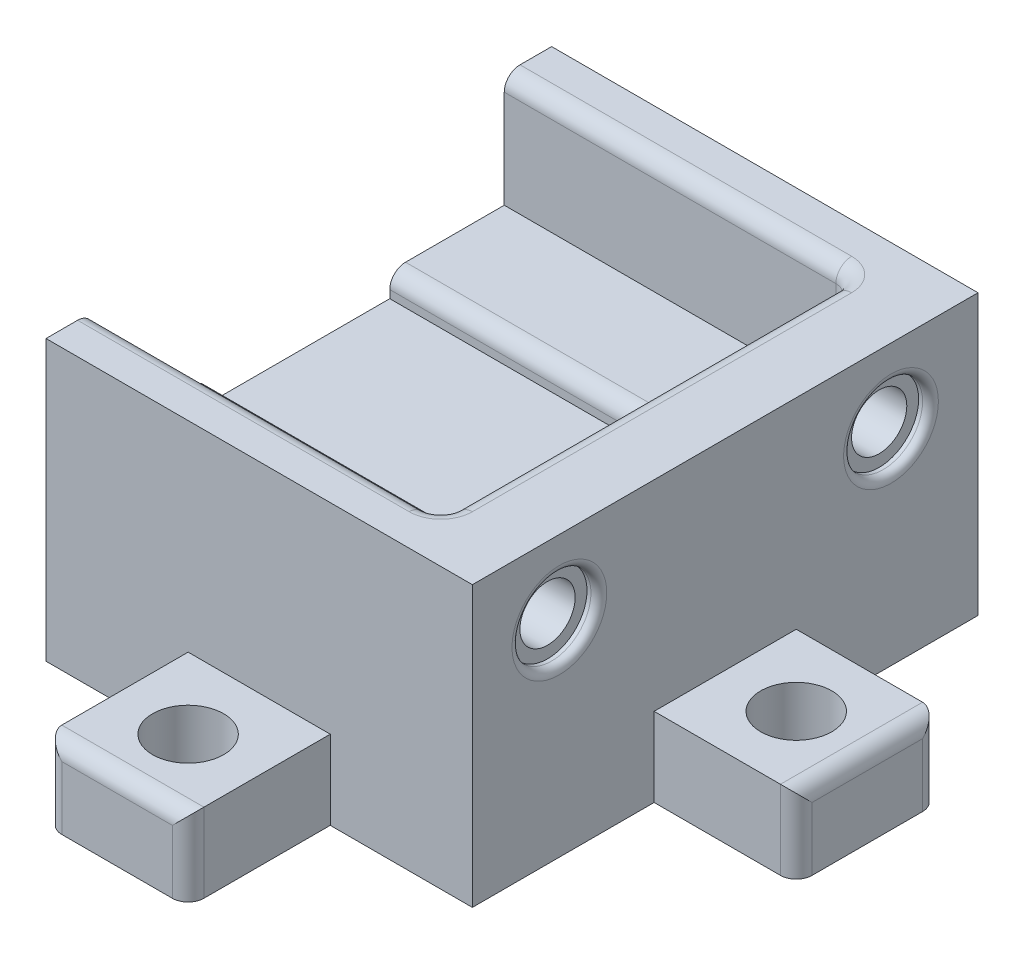
SolidWorks part; units mm, degrees
ref_plane "Front" through (0, 0, 0) normal (0, 0, 1) x (1, 0, 0)
ref_plane "Top" through (0, 0, 0) normal (0, 1, 0) x (1, 0, 0)
ref_plane "Right" through (0, 0, 0) normal (1, 0, 0) x (0, 0, -1)
sketch "Sketch1" plane through (0, 0, 0) normal (1, 0, 0) x (0, 0, -1)
  line L0 (-13.0089, 0) -> (13.0089, 0)
  line L1 (13.0089, 0) -> (13.0089, 10.5)
  line L2 (13.0089, 10.5) -> (5.7589, 10.5)
  line L3 (5.7589, 10.5) -> (5.7589, 9)
  line L4 (5.7589, 9) -> (-5.7589, 9)
  line L5 (-5.7589, 9) -> (-5.7589, 10.5)
  line L6 (-5.7589, 10.5) -> (-13.0089, 10.5)
  line L7 (-13.0089, 10.5) -> (-13.0089, 0)
  dimension "D1" = 10.5
  dimension "D2" = 7.25
  dimension "D3" = 26.0178
  dimension "D4" = 1.5
extrude "Boss-Extrude1" add sketch "Sketch1" along normal mid plane 22
sketch "Sketch3" plane through (0, 0, 0) normal (0, -1, 0) x (1, 0, 0)
  line L1 (-11, -13.0089) -> (11, -13.0089)
  line L2 (-11, -13.0089) -> (-11, -16.0089)
  line L3 (-11, -16.0089) -> (11, -16.0089)
  line L4 (11, -13.0089) -> (11, -16.0089)
  line L5 (-11, 13.0089) -> (11, 13.0089)
  line L6 (-11, 13.0089) -> (-11, 16.0089)
  line L7 (-11, 16.0089) -> (11, 16.0089)
  line L8 (11, 13.0089) -> (11, 16.0089)
  dimension "D1" = 3
  dimension "D2" = 22
  dimension "D3" = 3
  dimension "D4" = 22
extrude "Boss-Extrude2" add sketch "Sketch3" against normal blind 17.7
sketch "Sketch4" plane through (11, 0, 0) normal (1, 0, 0) x (0, 0, -1)
  line L0 (0, 0) -> (0, 17.7) construction
  line L1 (-16.0089, 0) -> (16.0089, 0) construction
  line L2 (-8.8, 17.7) -> (-16.0089, 17.7)
  line L3 (-16.0089, 17.7) -> (-16.0089, 0) construction
  line L4 (-16.0089, 17.7) -> (-16.0089, 0)
  line L5 (-16.0089, 0) -> (16.0089, 0)
  line L6 (16.0089, 0) -> (16.0089, 17.7)
  line L7 (16.0089, 17.7) -> (16.0089, 0) construction
  line L8 (16.0089, 17.7) -> (-8.8, 17.7)
extrude "Boss-Extrude3" add sketch "Sketch4" along normal blind 5
sketch "Sketch5" plane through (16, 0, 0) normal (1, 0, 0) x (0, 0, -1)
  line L0 (-16.0089, 13) -> (-10.5, 13) construction
  line L1 (-16.0089, 17.7) -> (-16.0089, 0) construction
  line L2 (-10.5, 13) -> (-10.5, 0) construction
  line L3 (-16.0089, 0) -> (16.0089, 0) construction
  line L4 (0, 0) -> (0, 17.7) construction
  line L5 (16.0089, 17.7) -> (-16.0089, 17.7) construction
  circle A0 centre (-10.5, 13) radius 1.75
  circle A1 centre (10.5, 13) radius 1.75
  dimension "D3" = 3.5
  dimension "D1" = 5.5089
  dimension "D2" = 13
extrude "Cut-Extrude1" cut sketch "Sketch5" against normal through all
sketch "Sketch6" plane through (0, 0, 0) normal (0, -1, 0) x (1, 0, 0)
  line L0 (16, 16.0089) -> (16, -16.0089) construction
  line L5 (0, 0) -> (16, 0) construction
  line L13 (16, 4.5) -> (25, 4.5)
  line L15 (7, 16.0089) -> (-2, 16.0089)
  line L20 (7, 16.0089) -> (7, 25.0089)
  line L21 (7, 25.0089) -> (-2, 25.0089)
  line L22 (-2, 16.0089) -> (-2, 25.0089)
  line L23 (16, 4.5) -> (16, -4.5)
  line L24 (16, -4.5) -> (25, -4.5)
  line L25 (25, 4.5) -> (25, -4.5)
  line L26 (16, 16.0089) -> (-11, 16.0089) construction
  point P12 (2.5, 16.0089)
  dimension "D1" = 9
  dimension "D2" = 9
  dimension "D3" = 9
  dimension "D4" = 9
extrude "Boss-Extrude4" add sketch "Sketch6" against normal blind 5
sketch "Sketch7" plane through (0, 5, 0) normal (0, 1, 0) x (1, 0, 0)
  line L0 (25, 0) -> (7, 0) construction
  line L2 (2.5, -16.0089) -> (2.5, -25.0089) construction
  line L3 (20.5, 4.5) -> (20.5, -4.5) construction
  line L4 (-2, -16.0089) -> (7, -16.0089) construction
  line L5 (7, -25.0089) -> (-2, -25.0089) construction
  line L7 (7, -4.5) -> (7, 4.5) construction
  line L8 (25, 4.5) -> (25, -4.5) construction
  line L9 (-2, -20.5089) -> (7, -20.5089) construction
  line L10 (16, 4.5) -> (25, 4.5) construction
  line L11 (25, -4.5) -> (16, -4.5) construction
  line L12 (-2, -25.0089) -> (-2, -16.0089) construction
  line L15 (7, -16.0089) -> (7, -25.0089) construction
  circle A0 centre (20.5, 0) radius 2.25
  circle A1 centre (2.5, -20.5089) radius 2.25
  point P5 (7, 0)
  point P11 (25, 0)
  point P23 (2.5, -20.5089)
  point P29 (20.5, 4.5)
  dimension "D1" = 4.5
extrude "Cut-Extrude2" cut sketch "Sketch7" against normal through all
fillet "Fillet1" radius 1 13 edges at (2.5, 5, 25.0089) (0, 10.5, 5.7589) (0, 10.5, -5.7589) (25, 5, 0) (0, 17.7, 13.0089) (11, 17.7, 0) (0, 17.7, -13.0089) (11, 14.1, 13.0089) (11, 14.1, -13.0089) (25, 2.5, 4.5) (25, 2.5, -4.5) (7, 2.5, 25.0089) (-2, 2.5, 25.0089)
sketch "Sketch8" plane through (16, 0, 0) normal (1, 0, 0) x (0, 0, -1)
  circle A0 centre (-10.5, 13) radius 2.5
  circle A1 centre (10.5, 13) radius 2.5
  dimension "D1" = 5
extrude "Cut-Extrude3" cut sketch "Sketch8" against normal blind 0.75
fillet "Fillet2" radius 0.5 2 edges at (16, 13, -13) (16, 13, 8)
